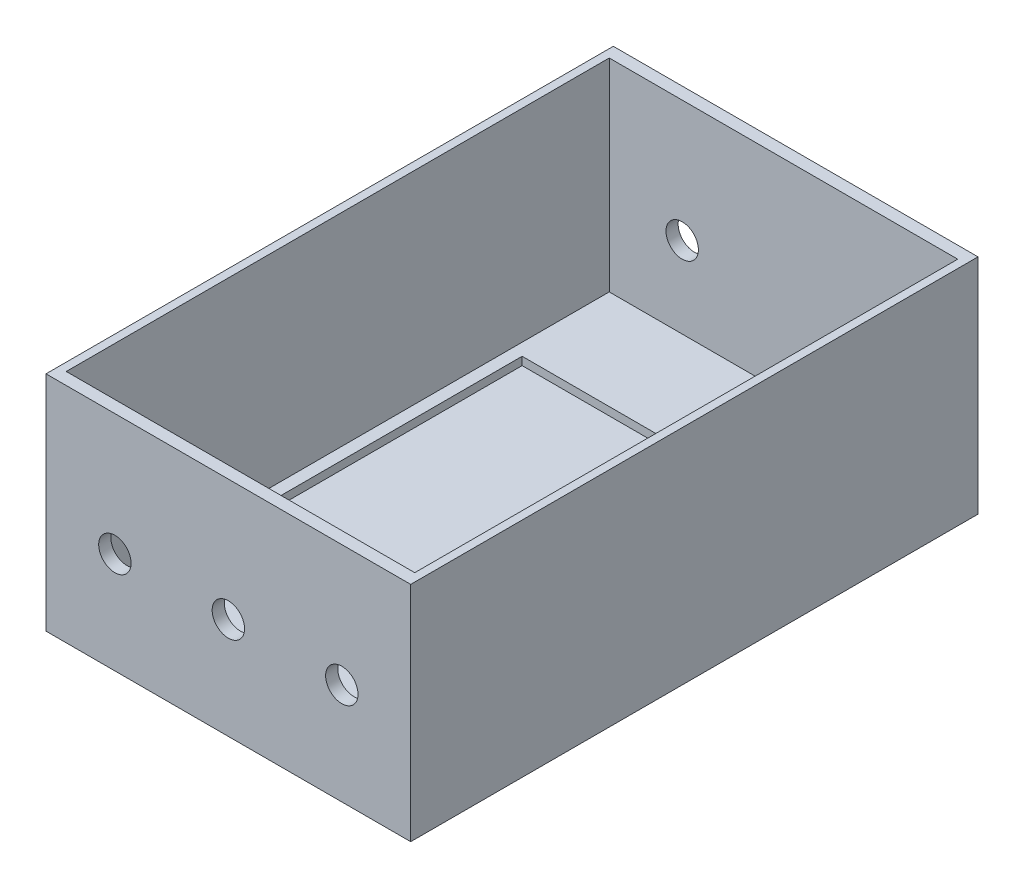
SolidWorks part; units mm, degrees
ref_plane "Front Plane" through (0, 0, 0) normal (0, 0, 1) x (1, 0, 0)
ref_plane "Top Plane" through (0, 0, 0) normal (0, 1, 0) x (1, 0, 0)
ref_plane "Right Plane" through (0, 0, 0) normal (1, 0, 0) x (0, 0, -1)
sketch "Sketch1" plane through (0, 0, 0) normal (0, 1, 0) x (1, 0, 0)
  line L1 (-45, -70) -> (45, -70)
  line L2 (-45, -70) -> (-45, 70)
  line L3 (-45, 70) -> (45, 70)
  line L4 (45, -70) -> (45, 70)
  line L5 (-45, -70) -> (45, 70) construction
  line L6 (-45, 70) -> (45, -70) construction
  point P0 (0, 0)
  dimension "D1" = 140
  dimension "D2" = 90
extrude "Boss-Extrude1" add sketch "Sketch1" along normal blind 5
sketch "Sketch2" plane through (0, 5, 0) normal (0, 1, 0) x (1, 0, 0)
  line L1 (-40, -42.5) -> (40, -42.5)
  line L2 (-40, -42.5) -> (-40, 42.5)
  line L3 (-40, 42.5) -> (40, 42.5)
  line L4 (40, -42.5) -> (40, 42.5)
  line L5 (-40, -42.5) -> (40, 42.5) construction
  line L6 (-40, 42.5) -> (40, -42.5) construction
  point P0 (0, 0)
  dimension "D1" = 85
  dimension "D2" = 80
extrude "Cut-Extrude1" cut sketch "Sketch2" against normal blind 2
sketch "Sketch3" plane through (0, 5, 0) normal (0, 1, 0) x (1, 0, 0)
  line L0 (45, -70) -> (45, 70) construction
  line L1 (-45, -70) -> (45, -70)
  line L2 (-45, -70) -> (-45, -67)
  line L3 (-45, -67) -> (45, -67)
  line L4 (45, -70) -> (45, -67)
  line L6 (-45, 70) -> (45, 70)
  line L7 (-45, 70) -> (-45, 67)
  line L8 (-45, 67) -> (45, 67)
  line L9 (45, 70) -> (45, 67)
  dimension "D1" = 3
  dimension "D2" = 3
extrude "Boss-Extrude2" add sketch "Sketch3" along normal blind 50
sketch "Sketch4" plane through (0, 5, 0) normal (0, 1, 0) x (1, 0, 0)
  line L0 (45, -67) -> (-45, -67) construction
  line L1 (-45, 67) -> (-43, 67)
  line L2 (-45, 67) -> (-45, -67)
  line L3 (-45, -67) -> (-43, -67)
  line L4 (-43, 67) -> (-43, -67)
  line L6 (45, 67) -> (43, 67)
  line L7 (45, 67) -> (45, -67)
  line L8 (45, -67) -> (43, -67)
  line L9 (43, 67) -> (43, -67)
  dimension "D1" = 2
  dimension "D2" = 2
extrude "Boss-Extrude3" add sketch "Sketch4" along normal blind 50
sketch "Sketch5" plane through (0, 0, 70) normal (0, 0, 1) x (1, 0, 0)
  line L0 (0, 0) -> (0, 25) construction
  line L1 (0, 25) -> (4, 25) construction
  line L2 (0, 25) -> (-4, 25) construction
  line L3 (-4, 25) -> (-24, 25) construction
  line L4 (-24, 25) -> (-28, 25) construction
  line L5 (-28, 25) -> (-32, 25) construction
  line L6 (4, 25) -> (24, 25) construction
  line L7 (24, 25) -> (28, 25) construction
  line L8 (28, 25) -> (32, 25) construction
  circle A0 centre (0, 25) radius 4
  circle A1 centre (28, 25) radius 4
  circle A2 centre (-28, 25) radius 4
  dimension "D1" = 25
  dimension "D2" = 4
  dimension "D3" = 20
extrude "Cut-Extrude2" cut sketch "Sketch5" against normal blind 3
sketch "Sketch6" plane through (0, 0, -70) normal (0, 0, -1) x (-1, 0, 0)
  line L0 (0, 0) -> (0, 25) construction
  line L1 (0, 25) -> (-25, 25) construction
  line L2 (0, 25) -> (25, 25) construction
  circle A0 centre (-25, 25) radius 4
  circle A1 centre (25, 25) radius 4
  dimension "D3" = 8
  dimension "D1" = 25
  dimension "D2" = 25
extrude "Cut-Extrude3" cut sketch "Sketch6" against normal blind 3
